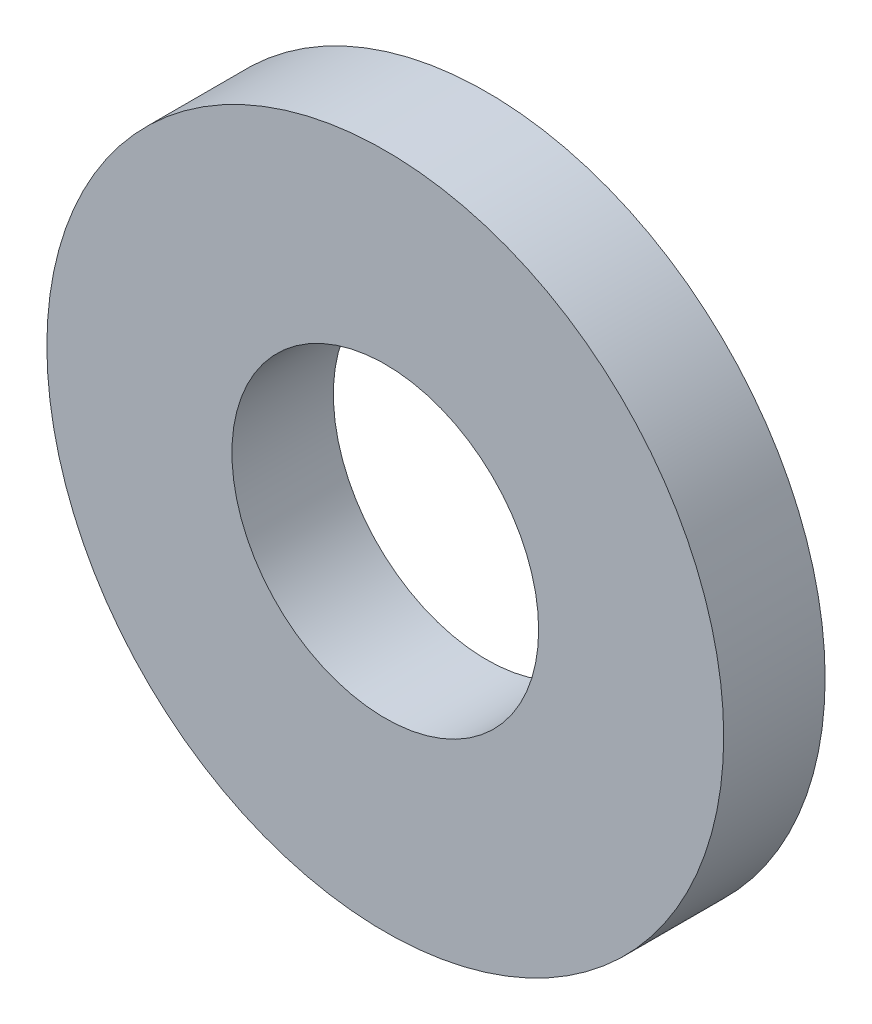
SolidWorks part; units mm, degrees
ref_plane "Front Plane" through (0, 0, 0) normal (0, 0, 1) x (1, 0, 0)
ref_plane "Top Plane" through (0, 0, 0) normal (0, 1, 0) x (1, 0, 0)
ref_plane "Right Plane" through (0, 0, 0) normal (1, 0, 0) x (0, 0, -1)
sketch "Sketch1" plane through (0, 0, 0) normal (0, 0, 1) x (1, 0, 0)
  circle A0 centre (0, 0) radius 2.3812
  circle A1 centre (0, 0) radius 5.2546
  dimension "D1" = 4.7625
  dimension "D2" = 10.5092
extrude "Boss-Extrude1" add sketch "Sketch1" along normal blind 1.5748
